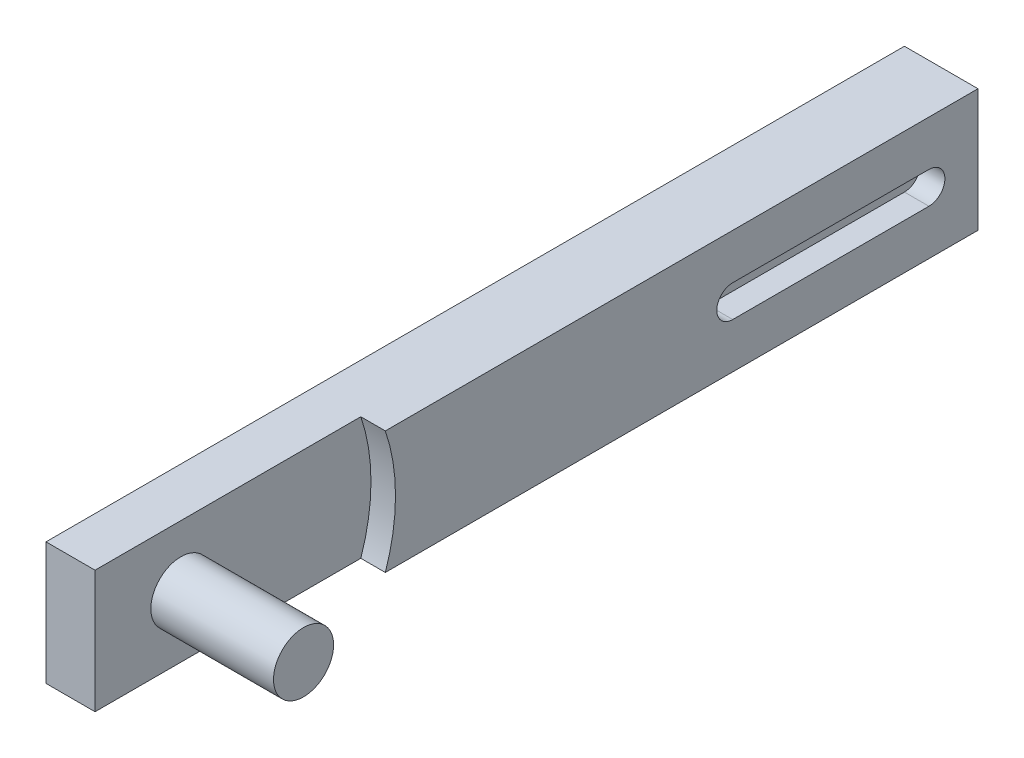
SolidWorks part; units mm, degrees
ref_plane "Front Plane" through (0, 0, 0) normal (0, 0, 1) x (1, 0, 0)
ref_plane "Top Plane" through (0, 0, 0) normal (0, 1, 0) x (1, 0, 0)
ref_plane "Right Plane" through (0, 0, 0) normal (1, 0, 0) x (0, 0, -1)
sketch "Sketch1" plane through (0, 0, 0) normal (1, 0, 0) x (0, 0, -1)
  line L1 (175, 25) -> (-175, 25)
  line L2 (175, 25) -> (175, -25)
  line L3 (175, -25) -> (-175, -25)
  line L4 (-175, 25) -> (-175, -25)
  line L5 (175, 25) -> (-175, -25) construction
  line L6 (175, -25) -> (-175, 25) construction
  point P0 (0, 0)
  dimension "D1" = 350
  dimension "D2" = 50
extrude "Boss-Extrude1" add sketch "Sketch1" along normal blind 30
sketch "Sketch2" plane through (30, 0, 0) normal (1, 0, 0) x (0, 0, -1)
  line L0 (155, 0) -> (75, 0) construction
  line L1 (155, -6.5) -> (75, -6.5)
  line L2 (155, 6.5) -> (75, 6.5)
  line L3 (175, -25) -> (175, 25) construction
  arc A0 (155, -6.5) -> (155, 6.5) centre (155, 0) ccw
  arc A1 (75, 6.5) -> (75, -6.5) centre (75, 0) ccw
  point P3 (115, 0)
  dimension "D3" = 6.5
  dimension "D1" = 80
  dimension "D2" = 100
extrude "Cut-Extrude1" cut sketch "Sketch2" against normal blind 10
sketch "Sketch3" plane through (30, 0, 0) normal (1, 0, 0) x (0, 0, -1)
  line L0 (-175, 25) -> (-175, -25) construction
  circle A0 centre (-140, 0) radius 77.5
  point P2 (0, 0)
  dimension "D1" = 155
  dimension "D2" = 35
extrude "Cut-Extrude2" cut sketch "Sketch3" against normal blind 10
sketch "Sketch4" plane through (20, 0, 0) normal (1, 0, 0) x (0, 0, -1)
  circle A0 centre (-140, 0) radius 12.25
  arc A1 (-66.643, -25) -> (-66.643, 25) centre (-140, 0) ccw construction
  dimension "D1" = 24.5
extrude "Boss-Extrude2" add sketch "Sketch4" along normal blind 50
sketch "Sketch5" plane through (0, 0, 0) normal (0, 1, 0) x (1, 0, 0)
  line L0 (20, -140) -> (30, -140) construction
  line L1 (20, -152.25) -> (20, -127.75) construction
  line L2 (30, -140) -> (105, -140)
  line L3 (105, -140) -> (183.6785, -185.4251)
  line L4 (20, -66.643) -> (20, -175) construction
  dimension "D1" = 75
  dimension "D2" = 85
  dimension "D3" = 150
